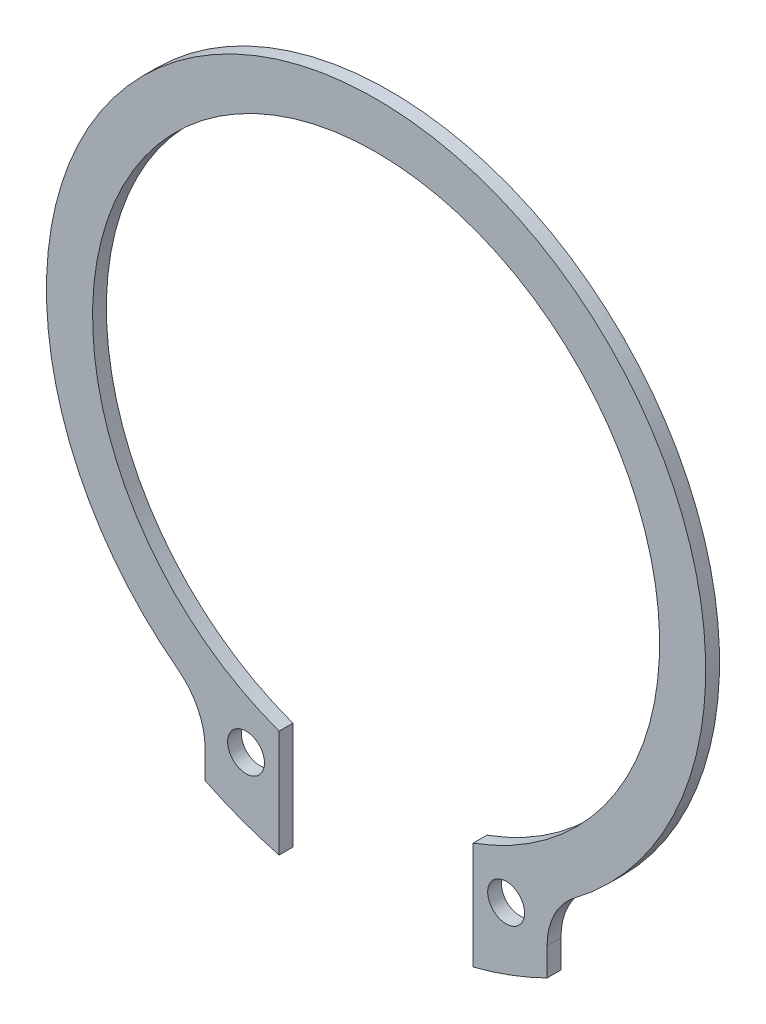
SolidWorks part; units mm, degrees
ref_plane "Front" through (0, 0, 0) normal (0, 0, 1) x (1, 0, 0)
ref_plane "Top" through (0, 0, 0) normal (0, 1, 0) x (1, 0, 0)
ref_plane "Right" through (0, 0, 0) normal (1, 0, 0) x (0, 0, -1)
sketch "Esquisse1" plane through (0, 0, 0) normal (0, 0, 1) x (1, 0, 0)
  line L0 (0, 0) -> (0, -96.1616) construction
  line L1 (0, 0) -> (-21.0342, -57.7911) construction
  line L2 (-21.0342, -57.7911) -> (-21.0342, -81.0724)
  line L3 (0, 0) -> (21.0342, -57.7911) construction
  line L4 (21.0342, -57.7911) -> (21.0342, -81.0724)
  line L5 (-37.0912, -75.0961) -> (-37.0912, -69.0562)
  line L6 (37.0912, -75.0961) -> (37.0912, -69.0562)
  arc A0 (21.0342, -57.7911) -> (-21.0342, -57.7911) centre (0, 0) ccw
  arc A2 (-21.0342, -81.0724) -> (-37.0912, -75.0961) centre (0, 0) cw
  circle A3 centre (-28.2027, -65.3715) radius 4
  arc A4 (-37.0912, -69.0562) -> (-43.058, -57.0811) centre (-52.0912, -69.0562) ccw
  arc A5 (21.0342, -81.0724) -> (37.0912, -75.0961) centre (0, 0) ccw
  arc A6 (37.0912, -69.0562) -> (43.058, -57.0811) centre (52.0912, -69.0562) cw
  arc A7 (43.058, -57.0811) -> (-43.058, -57.0811) centre (0, 0) ccw
  circle A8 centre (28.2027, -65.3715) radius 4
  dimension "D2" = 123
  dimension "D4" = 15
  dimension "D1" = 8
  dimension "D3" = 20
extrude "Boss.-Extru.1" add sketch "Esquisse1" along normal blind 3
